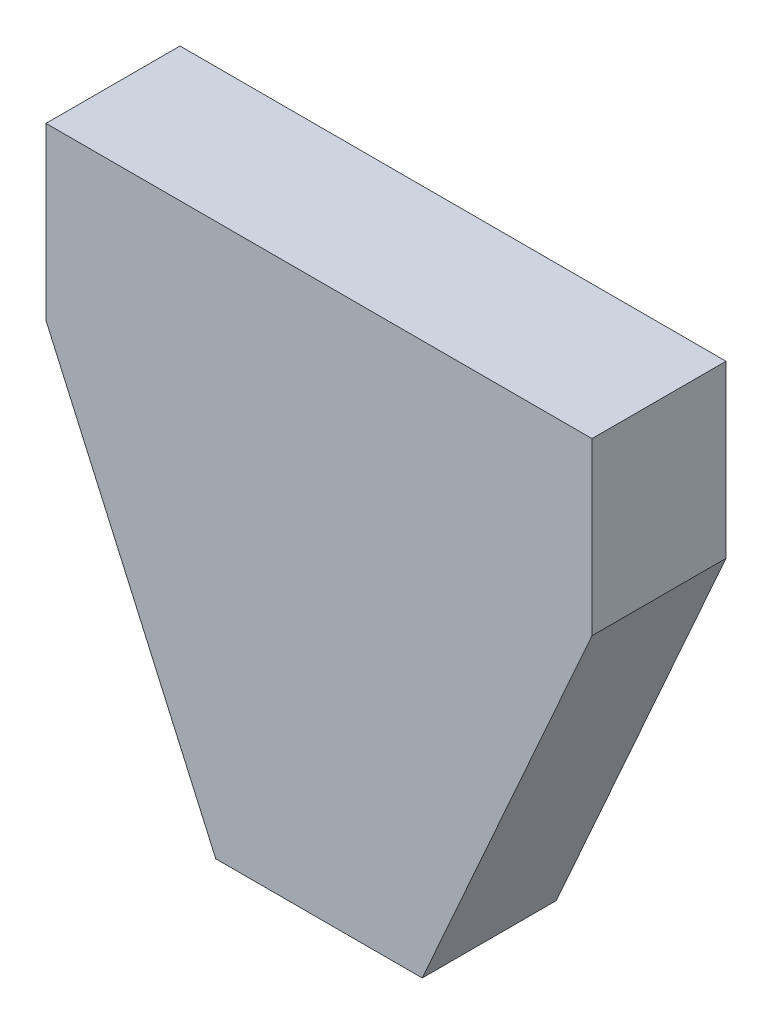
SolidWorks part; units mm, degrees
ref_plane "Front Plane" through (0, 0, 0) normal (0, 0, 1) x (1, 0, 0)
ref_plane "Top Plane" through (0, 0, 0) normal (0, 1, 0) x (1, 0, 0)
ref_plane "Right Plane" through (0, 0, 0) normal (1, 0, 0) x (0, 0, -1)
sketch "Sketch1" plane through (0, 0, 0) normal (0, 0, 1) x (1, 0, 0)
  line L0 (0, -0.3127) -> (0, -17128.7022) construction
  line L1 (0, 0) -> (17128.3896, 0) construction
  line L2 (550, 500) -> (-550, 500)
  line L3 (-550, 500) -> (-550, 156)
  line L4 (-550, 156) -> (-208, -612.1446)
  line L5 (-208, -612.1446) -> (208, -612.1446)
  line L6 (550, 156) -> (208, -612.1446)
  line L7 (550, 500) -> (550, 156)
  point P11 (0, -612.1446)
  point P13 (0, 500)
  dimension "D1" = 550
  dimension "D2" = 344
  dimension "D3" = 208
  dimension "D4" = 500
  dimension "D5" = 114
extrude "Boss-Extrude1" add sketch "Sketch1" along normal mid plane 270
shell "Shell1" thickness 2
